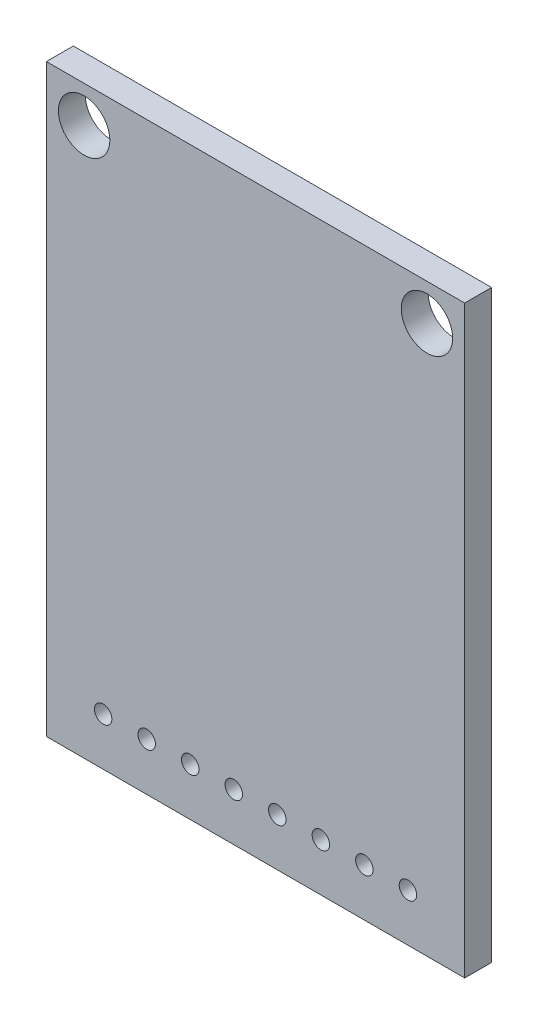
SolidWorks part; units mm, degrees
ref_plane "Přední rovina" through (0, 0, 0) normal (0, 0, 1) x (1, 0, 0)
ref_plane "Horní rovina" through (0, 0, 0) normal (0, 1, 0) x (1, 0, 0)
ref_plane "Pravá rovina" through (0, 0, 0) normal (1, 0, 0) x (0, 0, -1)
sketch "Sketch1" plane through (0, 0, 0) normal (0, 0, 1) x (1, 0, 0)
  line L0 (-10, 14.92) -> (10, 14.92) construction
  line L1 (-12.2, 17.05) -> (12.2, 17.05)
  line L2 (-12.2, 17.05) -> (-12.2, -17.05)
  line L3 (-12.2, -17.05) -> (12.2, -17.05)
  line L4 (12.2, 17.05) -> (12.2, -17.05)
  line L5 (-12.2, 17.05) -> (12.2, -17.05) construction
  line L6 (-12.2, -17.05) -> (12.2, 17.05) construction
  line L7 (-8.7547, -14.26) -> (7.8161, -14.26) construction
  circle A0 centre (-10, 14.92) radius 1.5
  circle A1 centre (10, 14.92) radius 1.5
  circle A2 centre (-8.89, -14.26) radius 0.51
  circle A3 centre (-6.35, -14.26) radius 0.51
  circle A4 centre (-3.81, -14.26) radius 0.51
  circle A5 centre (-1.27, -14.26) radius 0.51
  circle A6 centre (1.27, -14.26) radius 0.51
  circle A7 centre (3.81, -14.26) radius 0.51
  circle A8 centre (6.35, -14.26) radius 0.51
  circle A9 centre (8.89, -14.26) radius 0.51
  point P0 (0, 0)
  dimension "D3" = 3
  dimension "D4" = 3
  dimension "D9" = 1.02
  dimension "D1" = 34.1
  dimension "D2" = 24.4
  dimension "D5" = 20
  dimension "D6" = 2.2
  dimension "D7" = 2.2
  dimension "D8" = 2.13
  dimension "D11" = 2.79
  dimension "D12" = 3.31
  dimension "D13" = 3.31
  dimension "D14" = 1.27
  dimension "D10" = 8
extrude "Boss-Extrude1" add sketch "Sketch1" along normal blind 1.57
